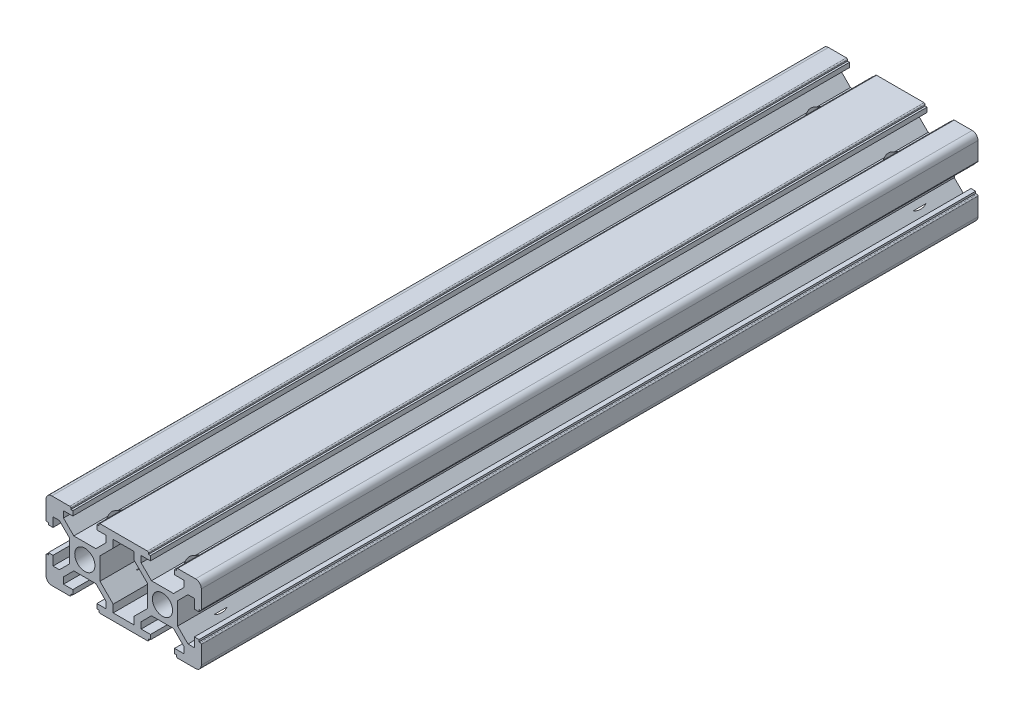
SolidWorks part; units mm, degrees
ref_plane "前视基准面" through (0, 0, 0) normal (0, 0, 1) x (1, 0, 0)
ref_plane "上视基准面" through (0, 0, 0) normal (0, 1, 0) x (1, 0, 0)
ref_plane "右视基准面" through (0, 0, 0) normal (1, 0, 0) x (0, 0, -1)
sketch "草图1" plane through (0, 0, 0) normal (0, 0, 1) x (1, 0, 0)
  line L0 (0, 0) -> (0, -41497.3383) construction
  line L1 (0, 0) -> (41497.3383, 0) construction
  line L2 (-13.9, 0) -> (-13.9, 2.8393)
  line L3 (-13.9, 2.8393) -> (-16.5607, 5.5)
  line L4 (-16.5607, 5.5) -> (-18.2, 5.5)
  line L5 (-18.2, 5.5) -> (-18.2, 3.1)
  line L6 (-18.2, 3.1) -> (-19.4, 3.1)
  line L7 (-19.4, 3.1) -> (-19.4, 3.6)
  line L8 (-19.4, 3.6) -> (-20, 3.6)
  line L9 (-20, 3.6) -> (-20, 10)
  line L10 (-20, 10) -> (-13.6, 10)
  line L11 (-13.6, 10) -> (-13.6, 9.4)
  line L12 (-13.6, 9.4) -> (-13.1, 9.4)
  line L13 (-13.1, 9.4) -> (-13.1, 8.2)
  line L14 (-13.1, 8.2) -> (-15.5, 8.2)
  line L15 (-15.5, 6.5607) -> (-12.8393, 3.9)
  line L16 (-12.8393, 3.9) -> (-7.1607, 3.9)
  line L17 (-4.5, 6.5607) -> (-7.1607, 3.9)
  line L18 (-4.5, 6.5607) -> (-4.5, 8.2)
  line L19 (-4.5, 8.2) -> (-6.9, 8.2)
  line L20 (-6.9, 8.2) -> (-6.9, 9.4)
  line L21 (-6.9, 9.4) -> (-6.4, 9.4)
  line L22 (-6.4, 9.4) -> (-6.4, 10)
  line L23 (-6.4, 10) -> (6.4, 10)
  line L24 (-15.5, 8.2) -> (-15.5, 6.5607)
  line L25 (-10, 0) -> (-20, 10) construction
  line L26 (-6.1, -2.8393) -> (-6.1, 2.8393)
  line L27 (-6.1, 2.8393) -> (-2.7, 6.2393)
  line L28 (-2.7, 6.2393) -> (-2.7, 8.2)
  line L29 (-2.7, 8.2) -> (2.7, 8.2)
  line L30 (-10, 0) -> (0, 10) construction
  line L31 (13.9, 0) -> (13.9, 2.8393)
  line L32 (6.1, -2.8393) -> (6.1, 2.8393)
  line L33 (4.5, 6.5607) -> (7.1607, 3.9)
  line L34 (12.8393, 3.9) -> (7.1607, 3.9)
  line L35 (6.1, 2.8393) -> (2.7, 6.2393)
  line L36 (2.7, 6.2393) -> (2.7, 8.2)
  line L37 (4.5, 6.5607) -> (4.5, 8.2)
  line L38 (6.4, 9.4) -> (6.4, 10)
  line L39 (6.9, 9.4) -> (6.4, 9.4)
  line L40 (6.9, 8.2) -> (6.9, 9.4)
  line L41 (4.5, 8.2) -> (6.9, 8.2)
  line L42 (13.1, 9.4) -> (13.1, 8.2)
  line L43 (13.6, 9.4) -> (13.1, 9.4)
  line L44 (13.6, 10) -> (13.6, 9.4)
  line L45 (20, 10) -> (13.6, 10)
  line L46 (20, 3.6) -> (20, 10)
  line L47 (19.4, 3.6) -> (20, 3.6)
  line L48 (19.4, 3.1) -> (19.4, 3.6)
  line L49 (18.2, 3.1) -> (19.4, 3.1)
  line L50 (18.2, 5.5) -> (18.2, 3.1)
  line L51 (16.5607, 5.5) -> (18.2, 5.5)
  line L52 (13.9, 2.8393) -> (16.5607, 5.5)
  line L53 (15.5, 6.5607) -> (12.8393, 3.9)
  line L54 (15.5, 8.2) -> (15.5, 6.5607)
  line L55 (13.1, 8.2) -> (15.5, 8.2)
  line L56 (15.5, -6.5607) -> (12.8393, -3.9)
  line L57 (13.9, -2.8393) -> (16.5607, -5.5)
  line L58 (16.5607, -5.5) -> (18.2, -5.5)
  line L59 (18.2, -5.5) -> (18.2, -3.1)
  line L60 (18.2, -3.1) -> (19.4, -3.1)
  line L61 (19.4, -3.1) -> (19.4, -3.6)
  line L62 (19.4, -3.6) -> (20, -3.6)
  line L63 (12.8393, -3.9) -> (7.1607, -3.9)
  line L64 (13.9, 0) -> (13.9, -2.8393)
  line L65 (13.1, -8.2) -> (15.5, -8.2)
  line L66 (15.5, -8.2) -> (15.5, -6.5607)
  line L67 (20, -3.6) -> (20, -10)
  line L68 (20, -10) -> (13.6, -10)
  line L69 (13.6, -10) -> (13.6, -9.4)
  line L70 (13.6, -9.4) -> (13.1, -9.4)
  line L71 (13.1, -9.4) -> (13.1, -8.2)
  line L72 (4.5, -8.2) -> (6.9, -8.2)
  line L73 (6.9, -8.2) -> (6.9, -9.4)
  line L74 (6.9, -9.4) -> (6.4, -9.4)
  line L75 (6.4, -9.4) -> (6.4, -10)
  line L76 (4.5, -6.5607) -> (4.5, -8.2)
  line L77 (2.7, -6.2393) -> (2.7, -8.2)
  line L78 (6.1, -2.8393) -> (2.7, -6.2393)
  line L79 (4.5, -6.5607) -> (7.1607, -3.9)
  line L80 (-2.7, -8.2) -> (2.7, -8.2)
  line L81 (-2.7, -6.2393) -> (-2.7, -8.2)
  line L82 (-6.1, -2.8393) -> (-2.7, -6.2393)
  line L83 (-4.5, -6.5607) -> (-7.1607, -3.9)
  line L84 (-4.5, -8.2) -> (-6.9, -8.2)
  line L85 (-4.5, -6.5607) -> (-4.5, -8.2)
  line L86 (-6.4, -10) -> (6.4, -10)
  line L87 (-6.4, -9.4) -> (-6.4, -10)
  line L88 (-6.9, -9.4) -> (-6.4, -9.4)
  line L89 (-6.9, -8.2) -> (-6.9, -9.4)
  line L90 (-13.1, -9.4) -> (-13.1, -8.2)
  line L91 (-13.6, -9.4) -> (-13.1, -9.4)
  line L92 (-13.6, -10) -> (-13.6, -9.4)
  line L93 (-15.5, -8.2) -> (-15.5, -6.5607)
  line L94 (-13.1, -8.2) -> (-15.5, -8.2)
  line L95 (-12.8393, -3.9) -> (-7.1607, -3.9)
  line L96 (-15.5, -6.5607) -> (-12.8393, -3.9)
  line L97 (-13.9, 0) -> (-13.9, -2.8393)
  line L98 (-13.9, -2.8393) -> (-16.5607, -5.5)
  line L99 (-19.4, -3.6) -> (-20, -3.6)
  line L100 (-19.4, -3.1) -> (-19.4, -3.6)
  line L101 (-18.2, -3.1) -> (-19.4, -3.1)
  line L102 (-18.2, -5.5) -> (-18.2, -3.1)
  line L103 (-16.5607, -5.5) -> (-18.2, -5.5)
  line L104 (-20, -3.6) -> (-20, -10)
  line L105 (-20, -10) -> (-13.6, -10)
  circle A0 centre (-10, 0) radius 2.6
  circle A1 centre (10, 0) radius 2.6
  point P50 (0, 8.2)
  point P95 (6.1, 0)
  point P96 (-6.1, 0)
  dimension "D1" = 5.2
  dimension "D2" = 45
  dimension "D3" = 1.5
  dimension "D4" = 20
  dimension "D5" = 40
  dimension "D6" = 0.75
  dimension "D7" = 7.2
  dimension "D8" = 6.2
  dimension "D9" = 6.1
  dimension "D10" = 1.8
  dimension "D11" = 1.2
  dimension "D12" = 12.2
  dimension "D13" = 5.4
  dimension "D14" = 11
  dimension "D15" = 1.5
  dimension "D16" = 0.75
extrude "凸台-拉伸1" add sketch "草图1" along normal mid plane 200
fillet "圆角1" radius 1.5 4 edges at (20, -10, 0) (20, 10, 0) (-20, -10, 0) (-20, 10, 0)
fillet "圆角2" radius 0.3 12 edges at (-6.4, 10, 0) (-13.6, 10, 0) (-20, 3.6, 0) (-20, -3.6, 0) (-13.6, -10, 0) (-6.4, -10, 0) (6.4, -10, 0) (20, -3.6, 0) (20, 3.6, 0) (13.6, -10, 0) (13.6, 10, 0) (6.4, 10, 0)
sketch "草图3" plane through (0, -3.9, 0) normal (0, -1, 0) x (1, 0, 0)
  line L5 (12.8393, -100) -> (7.1607, -100) construction
  line L6 (10, -90) -> (-10, -90) construction
  circle A8 centre (10, -90) radius 3.1
  circle A9 centre (-10, -90) radius 3.1
  circle A10 centre (10, 90) radius 3.1
  circle A11 centre (-10, 90) radius 3.1
  point P29 (0, -90)
  dimension "D7" = 10
  dimension "D8" = 6.2
  dimension "D11" = 180
  dimension "D9" = 20
  dimension "D10" = 2
extrude "切除-拉伸1" cut sketch "草图3" against normal through all both and the other way through all
sketch "草图5" plane through (0, -3.9, 0) normal (0, -1, 0) x (1, 0, 0)
  circle A0 centre (10, -90) radius 5.25
  circle A1 centre (-10, -90) radius 5.25
  circle A2 centre (10, 90) radius 5.25
  circle A3 centre (-10, 90) radius 5.25
  dimension "D1" = 10.5
extrude "切除-拉伸3" cut sketch "草图5" along normal through all
equation "\"D6@草图1\"=1/2*\"D3@草图1\""
equation "\"D16@草图1\"=0.5*\"D15@草图1\""
